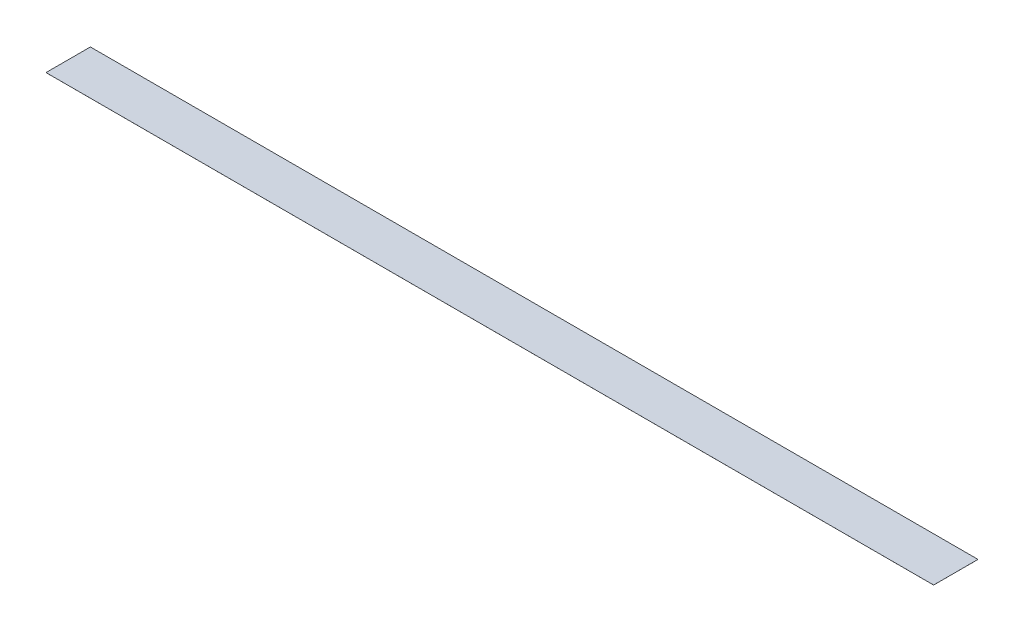
SolidWorks part; units mm, degrees
ref_plane "Plano frontal" through (0, 0, 0) normal (0, 0, 1) x (1, 0, 0)
ref_plane "Plano superior" through (0, 0, 0) normal (0, 1, 0) x (1, 0, 0)
ref_plane "Plano direito" through (0, 0, 0) normal (1, 0, 0) x (0, 0, -1)
sketch "Esboço1" plane through (0, 0, 0) normal (0, 1, 0) x (1, 0, 0)
  line L0 (-1093, 595.536) -> (-1073, 595.536)
  line L1 (0, 0) -> (18.9344, 0)
  line L2 (0, 0) -> (0, 766.8662)
  line L3 (0, 766.8662) -> (18.9344, 766.8662)
  line L4 (18.9344, 0) -> (18.9344, 766.8662)
  line L5 (-381.6968, 766.8662) -> (-362.7624, 766.8662)
  line L6 (-381.6968, 766.8662) -> (-381.6968, 345.536)
  line L7 (-381.6968, 345.536) -> (-362.7624, 345.536)
  line L8 (-362.7624, 766.8662) -> (-362.7624, 345.536)
  line L9 (-858.9344, 645.536) -> (-840, 645.536)
  line L10 (-858.9344, 645.536) -> (-858.9344, 345.536)
  line L11 (-858.9344, 345.536) -> (-840, 345.536)
  line L12 (-840, 645.536) -> (-840, 345.536)
  line L13 (-853.5858, 925.2213) -> (-1253.5858, 925.2213)
  line L14 (-853.5858, 925.2213) -> (-853.5858, 945.2213)
  line L15 (-853.5858, 945.2213) -> (-1253.5858, 945.2213)
  line L16 (-1253.5858, 925.2213) -> (-1253.5858, 945.2213)
  line L17 (-1093, 595.536) -> (-1093, 195.536)
  line L18 (-1093, 195.536) -> (-1073, 195.536)
  line L19 (-1073, 595.536) -> (-1073, 195.536)
  line L21 (-858.9344, 427.7897) -> (-1250.0103, 427.7897)
  line L23 (-858.9344, 407.7897) -> (-1250.0103, 407.7897)
  line L24 (-1250.0103, 427.7897) -> (-1250.0103, 407.7897)
  line L33 (-1439.6613, 239.7512) -> (-1560.0448, 239.7512)
  line L34 (-1439.6613, 239.7512) -> (-1439.6613, 219.7512)
  line L35 (-1439.6613, 219.7512) -> (-1560.0448, 219.7512)
  line L36 (-1560.0448, 239.7512) -> (-1560.0448, 219.7512)
  line L37 (-1627.2015, 576.144) -> (-1607.2015, 576.144)
  line L38 (-1627.2015, 576.144) -> (-1627.2015, 317.0654)
  line L39 (-1627.2015, 317.0654) -> (-1607.2015, 317.0654)
  line L40 (-1607.2015, 576.144) -> (-1607.2015, 317.0654)
  line L41 (-1627.2015, 769.6927) -> (-1607.2015, 769.6927)
  line L42 (-1627.2015, 769.6927) -> (-1627.2015, 1019.6927)
  line L43 (-1627.2015, 1019.6927) -> (-1607.2015, 1019.6927)
  line L44 (-1607.2015, 769.6927) -> (-1607.2015, 1019.6927)
  line L45 (694.2768, 1067.5028) -> (294.2768, 1067.5028)
  line L46 (694.2768, 1067.5028) -> (694.2768, 1087.5028)
  line L47 (694.2768, 1087.5028) -> (294.2768, 1087.5028)
  line L48 (294.2768, 1067.5028) -> (294.2768, 1087.5028)
  arc A6 (-381.6968, 766.8662) -> (18.9344, 766.8662) centre (-181.3812, 766.8662) cw
  arc A7 (-362.7624, 766.8662) -> (0, 766.8662) centre (-181.3812, 766.8662) cw
  arc A8 (-362.7624, 345.536) -> (-858.9344, 345.536) centre (-610.8484, 345.536) cw
  arc A9 (-381.6968, 345.536) -> (-840, 345.536) centre (-610.8484, 345.536) cw
  arc A10 (-840, 645.536) -> (-803.6955, 702.0415) centre (-777.8744, 645.536) cw
  arc A11 (-803.6955, 702.0415) -> (-853.5858, 945.2213) centre (-856.6336, 817.8884) ccw
  arc A12 (-858.9344, 645.536) -> (-814.4955, 717.9247) centre (-777.7563, 645.536) cw
  arc A13 (-814.4955, 717.9247) -> (-853.5858, 925.2213) centre (-864.2122, 815.8835) ccw
  arc A14 (-1093, 595.536) -> (-1188.5366, 677.9223) centre (-1176.2913, 595.536) ccw
  arc A15 (-1188.5366, 677.9223) -> (-1354.3411, 742.8189) centre (-1214.8489, 854.9525) cw
  arc A16 (-1354.3411, 742.8189) -> (-1253.5858, 945.2213) centre (-1257.3278, 820.805) cw
  arc A17 (-1073, 595.536) -> (-1188.5366, 698.0004) centre (-1176.2038, 595.536) ccw
  arc A18 (-1188.5366, 698.0004) -> (-1341.8208, 766.8662) centre (-1207.9995, 859.705) cw
  arc A19 (-1341.8208, 766.8662) -> (-1253.5858, 925.2213) centre (-1258.876, 824.4093) cw
  arc A22 (-1368.7558, 309.7722) -> (-1439.6613, 219.7512) centre (-1474.849, 320.402) cw
  arc A23 (-1388.5562, 309.7722) -> (-1439.6613, 239.7512) centre (-1477.6183, 321.1143) cw
  arc A24 (-1388.5562, 309.7722) -> (-1250.0103, 427.7897) centre (-1254.4723, 292.6965) cw
  arc A25 (-1607.2015, 317.0654) -> (-1560.0448, 239.7512) centre (-1520.2441, 317.0654) ccw
  arc A26 (-1627.2015, 317.0654) -> (-1560.0448, 219.7512) centre (-1523.1159, 317.0654) ccw
  arc A27 (-1368.7558, 309.7722) -> (-1250.0103, 407.7897) centre (-1259.9289, 298.8686) cw
extrude "Ressalto-extrusão11" add sketch "Esboço1" along normal blind 0.01 contours L45 L48 L47 L46
